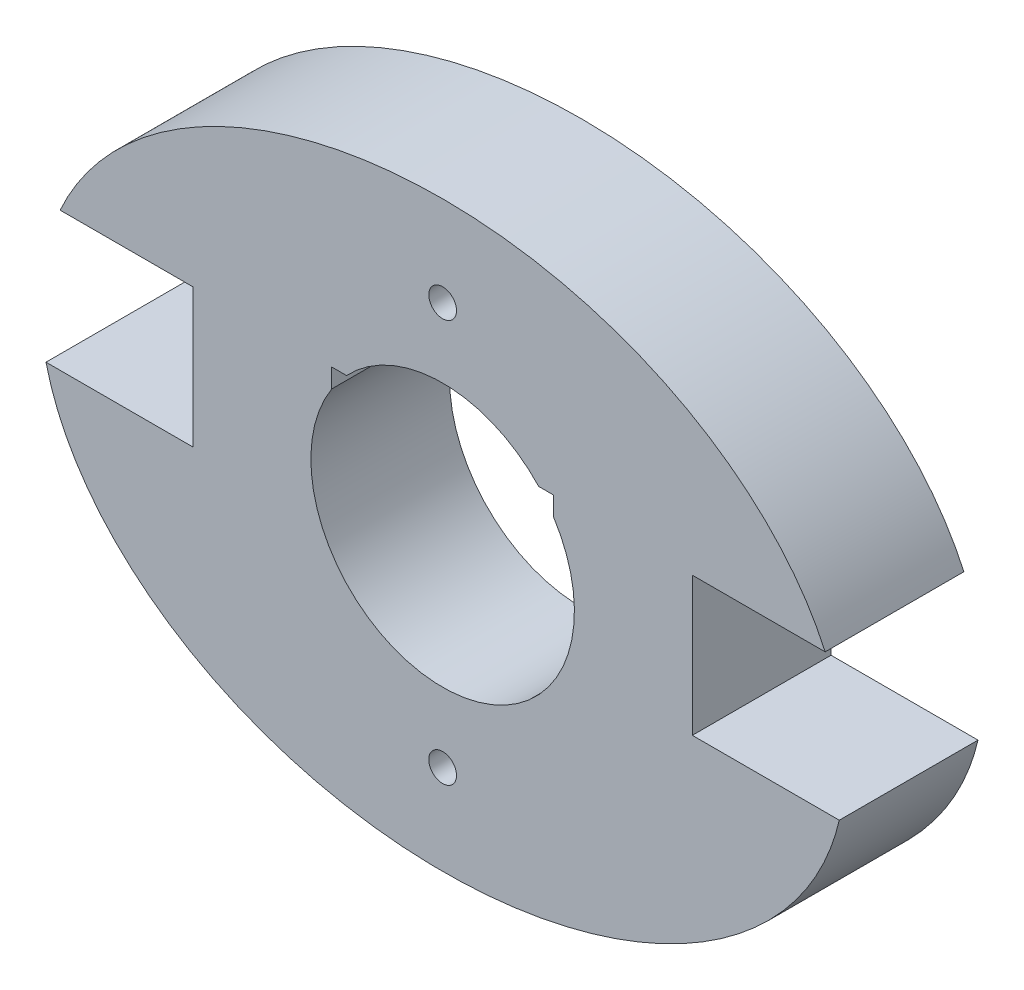
SolidWorks part; units mm, degrees
material "Balsa"
ref_plane "Plan de face" through (0, 0, 0) normal (0, 0, 1) x (1, 0, 0)
ref_plane "Plan de dessus" through (0, 0, 0) normal (0, 1, 0) x (1, 0, 0)
ref_plane "Plan de droite" through (0, 0, 0) normal (1, 0, 0) x (0, 0, -1)
sketch "Esquisse1" plane through (0, 0, 0) normal (0, 0, 1) x (1, 0, 0)
  line L0 (-20.8509, -1.75) -> (20.8509, -1.75) construction
  line L1 (0, 7.2545) -> (0, -7.2545) construction
  line L2 (-14.5, 0) -> (14.5, 0) construction
  line L3 (-20.8509, 3.25) -> (20.8509, 3.25) construction
  line L4 (20.8509, 3.25) -> (-20.8509, -1.75) construction
  line L5 (20.8509, -1.75) -> (-20.8509, 3.25) construction
  line L6 (-13.7879, 3.25) -> (-9, 3.25)
  line L7 (13.7879, 3.25) -> (9, 3.25)
  line L8 (14.2972, -1.75) -> (9, -1.75)
  line L9 (-14.2972, -1.75) -> (-9, -1.75)
  line L10 (-9, 3.25) -> (-9, -1.75)
  line L11 (9, 3.25) -> (9, -1.75)
  line L12 (15.2888, 0.75) -> (-16.9334, 0.75) construction
  circle A5 centre (0, 7.2545) radius 0.5
  circle A6 centre (0, -7.2545) radius 0.5
  circle A9 centre (0, 0) radius 4.75
  ellipse E0 centre (0, 0) end of major axis (14.5, 0) minor radius 10.5 (-13.7879, 3.25) -> (13.7879, 3.25) cw
  ellipse E1 centre (0, 0) end of major axis (14.5, 0) minor radius 10.5 (-14.2972, -1.75) -> (14.2972, -1.75) ccw
  point P1 (0, 0.75)
  dimension "D2" = 9.5
  dimension "D7" = 1
  dimension "D8" = 1
  dimension "D1" = 5
  dimension "D4" = 18
  dimension "D6" = 21
  dimension "D9" = 0.75
  dimension "D10" = 29
extrude "Boss.-Extru.1" add sketch "Esquisse1" along normal blind 5
sketch "Esquisse2" plane through (0, 0, 0) normal (0, 0, -1) x (-1, 0, 0)
  line L0 (-9, 3.25) -> (-13.7879, 3.25) construction
  line L1 (4, 3.25) -> (4, -1.75)
  line L2 (-4, 3.25) -> (-4, -1.75)
  line L3 (4, 3.25) -> (-4, 3.25)
  line L4 (-4, -1.75) -> (4, -1.75)
  line L5 (0, 0) -> (0, 18.2087) construction
  line L6 (-14.2972, -1.75) -> (-9, -1.75) construction
  dimension "D1" = 8
extrude "Enlèv. mat.-Extru.1" cut sketch "Esquisse2" against normal blind 5
